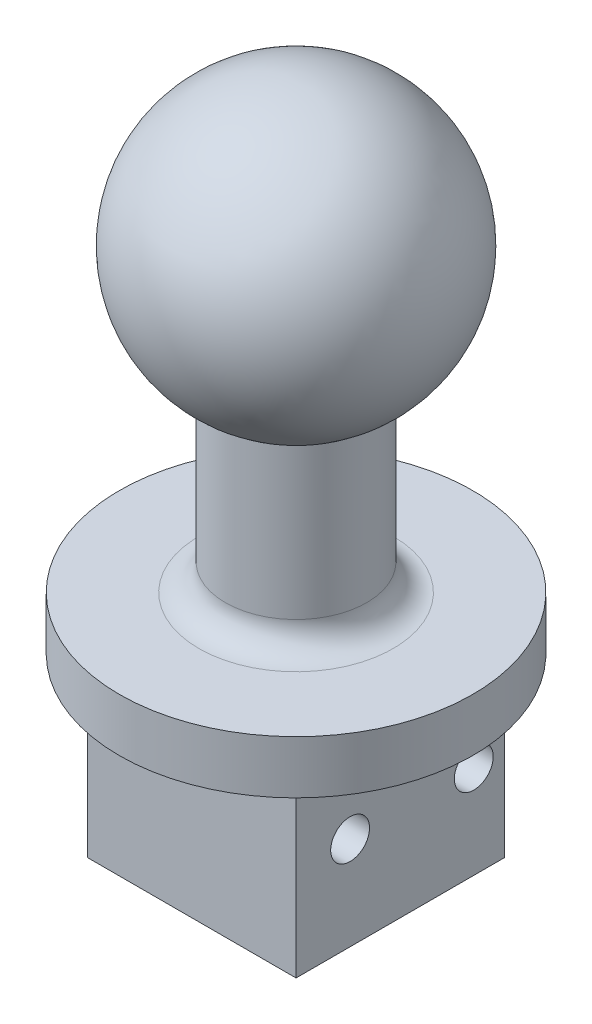
SolidWorks part; units mm, degrees
ref_plane "Front Plane" through (0, 0, 0) normal (0, 0, 1) x (1, 0, 0)
ref_plane "Top Plane" through (0, 0, 0) normal (0, 1, 0) x (1, 0, 0)
ref_plane "Right Plane" through (0, 0, 0) normal (1, 0, 0) x (0, 0, -1)
sketch "Sketch1" plane through (0, 0, 0) normal (0, 1, 0) x (1, 0, 0)
  line L1 (-5.9, 5.9) -> (5.9, 5.9)
  line L2 (-5.9, 5.9) -> (-5.9, -5.9)
  line L3 (-5.9, -5.9) -> (5.9, -5.9)
  line L4 (5.9, 5.9) -> (5.9, -5.9)
  line L5 (-5.9, 5.9) -> (5.9, -5.9) construction
  line L6 (-5.9, -5.9) -> (5.9, 5.9) construction
  point P0 (0, 0)
  dimension "D1" = 11.8
  dimension "D2" = 11.8
extrude "Boss-Extrude1" add sketch "Sketch1" along normal blind 10
sketch "Sketch2" plane through (0, 10, 0) normal (0, 1, 0) x (1, 0, 0)
  circle A0 centre (0, 0) radius 10
  dimension "D1" = 20
extrude "Boss-Extrude2" add sketch "Sketch2" along normal blind 3
sketch "Sketch3" plane through (0, 13, 0) normal (0, 1, 0) x (1, 0, 0)
  circle A0 centre (0, 0) radius 4
  dimension "D1" = 8
extrude "Boss-Extrude3" add sketch "Sketch3" along normal blind 15
sketch "Sketch4" plane through (0, 0, 0) normal (0, 0, 1) x (1, 0, 0)
  line L0 (0, 0) -> (0, 38) construction
  line L1 (0, 38) -> (0, 22)
  arc A0 (0, 22) -> (0, 38) centre (0, 30) ccw
  dimension "D1" = 16
  dimension "D2" = 30
revolve "Revolve1" add sketch "Sketch4" angle 360 about L0
fillet "Fillet1" radius 0.5 4 edges at (0, 10, -5.9) (5.9, 10, 0) (0, 10, 5.9) (-5.9, 10, 0)
fillet "Fillet2" radius 1.5 1 edges at (0, 13, 4)
sketch "Sketch6" plane through (5.9, 0, 0) normal (1, 0, 0) x (0, 0, -1)
  line L0 (-5.9, 0) -> (5.9, 0) construction
  line L2 (-5.9, 9.5) -> (-5.9, 0) construction
  circle A0 centre (-2.84, 5.28) radius 1.1
  circle A1 centre (4.16, 5.28) radius 1.1
  dimension "D1" = 2.2
  dimension "D3" = 2.2
  dimension "D4" = 5.28
  dimension "D2" = 7
  dimension "D5" = 3.06
extrude "Cut-Extrude1" cut sketch "Sketch6" against normal up to next
equation "\"board_w\"= 33.8"
equation "\"board_l\"= 41"
equation "\"stack_h\"= 19.5"
equation "\"module_w\"= 9.9"
equation "\"lens_d\"= 7.8"
equation "\"lens_from_end\"= 8"
equation "\"usb_w\"= 13"
equation "\"plug_h\"= 7"
equation "\"usb_from_back\"= 6"
equation "\"clear\"= 0.4"
equation "\"wall\"= 3"
equation "\"floor_t\"= 2.5"
equation "\"pocket_clear\"= 0.3"
equation "\"lens_clear\"= 0.6"
equation "\"plate_w\"= 16"
equation "\"plate_clear\"= 0.3"
equation "\"plate_t\"= 1.2"
equation "\"plate_seat\"= 0.8"
equation "\"window_d\"= 12"
equation "\"lid_t\"= 2"
equation "\"lid_gap\"= 1"
equation "\"groove_d\"= 1.2"
equation "\"groove_clear\"= 0.15"
equation "\"lip_top\"= 1.2"
equation "\"side_clear\"= 0.2"
equation "\"slide_clear\"= 0.2"
equation "\"ball_d\"= 16"
equation "\"ball_clear\"= 0.3"
equation "\"lip\"= 1.2"
equation "\"cup_floor\"= 1.2"
equation "\"cup_d\"= 26"
equation "\"slit_w\"= 1.5"
equation "\"slit_depth\"= 9"
equation "\"lug_w\"= 16"
equation "\"m3_hole\"= 3.4"
equation "\"m3_nut\"= 5.7"
equation "\"m3_nut_d\"= 2.6"
equation "\"boss_d\"= 20"
equation "\"boss_h\"= 8"
equation "\"nut_af\"= 11.4"
equation "\"nut_t\"= 5.8"
equation "\"screw_hole\"= 6.6"
equation "\"post_w\"= 30"
equation "\"post_len\"= 120"
equation "\"spigot_w\"= 23.7"
equation "\"bore_w\"= 24"
equation "\"spigot_len\"= 25"
equation "\"base_w\"= 130"
equation "\"base_h\"= 40"
equation "\"hole_depth\"= 30"
equation "\"base_clear\"= 0.4"
equation "\"base_col\"= 42"
equation "\"base_shell\"= 3"
equation "\"head_h\"= 50"
equation "\"arm_under\"= 30"
equation "\"arm_reach\"= 45"
equation "\"face_run\"= 20"
equation "\"bb_d\"= 24"
equation "\"bb_h\"= 10"
equation "\"neck_d\"= 8"
equation "\"ball_drop\"= 14"
equation "\"in_l\"= \"board_l\" + 2 * \"clear\""
equation "\"in_w\"= \"board_w\" + 2 * \"clear\""
equation "\"out_l\"= \"in_l\" + 2 * \"wall\""
equation "\"out_w\"= \"in_w\" + 2 * \"wall\""
equation "\"y_groove\"= \"floor_t\" - \"plate_seat\" + \"stack_h\" + \"lid_gap\""
equation "\"groove_h\"= \"lid_t\" + 2 * \"groove_clear\""
equation "\"tray_h\"= \"y_groove\" + \"groove_h\" + \"lip_top\""
equation "\"lid_w\"= \"in_w\" + 2 * \"groove_d\" - 2 * \"side_clear\""
equation "\"lid_right\"= \"in_l\" / 2 + \"groove_d\" - \"slide_clear\""
equation "\"lid_left\"= \"out_l\" / 2"
equation "\"open_d\"= \"ball_d\" - 2 * \"lip\""
equation "\"c_ball\"= sqr( ( ( \"ball_d\" + \"ball_clear\" ) / 2 ) ^ 2 - ( \"open_d\" / 2 ) ^ 2 )"
equation "\"cup_h\"= \"cup_floor\" + ( \"ball_d\" + \"ball_clear\" ) / 2 + \"c_ball\""
equation "\"lug_in\"= \"cup_d\" / 2 - 5"
equation "\"lug_out\"= \"cup_d\" / 2 + 4"
equation "\"peg_w\"=11.8"
equation "\"D1@Sketch1\"=\"peg_w\""
equation "\"peg_len\"=10"
equation "\"D1@Boss-Extrude1\"=\"peg_len\""
equation "\"shoulder_d\"=20"
equation "\"D1@Sketch2\"=\"shoulder_d\""
equation "\"shoulder_t\"=10"
equation "\"D1@Boss-Extrude2\"=3"
equation "\"D1@Sketch3\"=\"neck_d\""
equation "\"D1@Boss-Extrude3\"=\"ball_drop\" +1"
equation "\"D1@Sketch4\"=\"ball_d\""
equation "\"D2@Sketch4\"=30"
equation "\"D4@Sketch6\"=5-4.72+5"
equation "\"D5@Sketch6\"=2.2/2+1.96mm"
